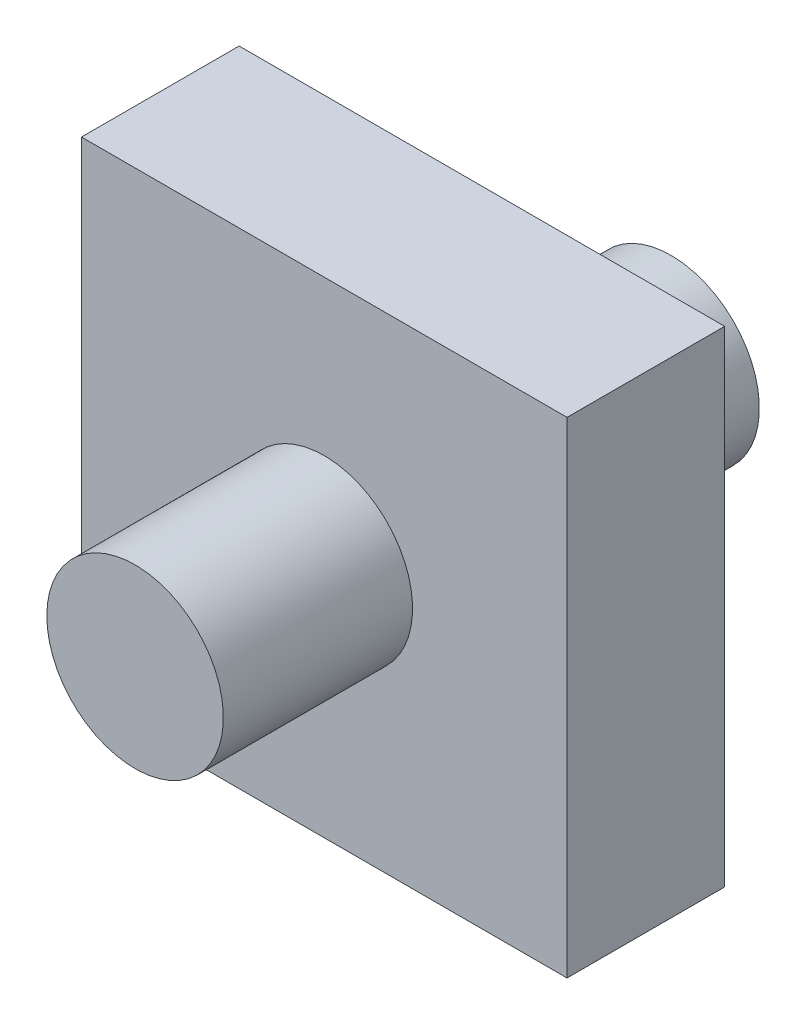
SolidWorks part; units mm, degrees
ref_plane "Alzado" through (0, 0, 0) normal (0, 0, 1) x (1, 0, 0)
ref_plane "Planta" through (0, 0, 0) normal (0, 1, 0) x (1, 0, 0)
ref_plane "Vista lateral" through (0, 0, 0) normal (1, 0, 0) x (0, 0, -1)
sketch "Croquis1" plane through (0, 0, 0) normal (0, 0, 1) x (1, 0, 0)
  line L1 (-3.85, -3.85) -> (3.85, -3.85)
  line L2 (-3.85, -3.85) -> (-3.85, 3.85)
  line L3 (-3.85, 3.85) -> (3.85, 3.85)
  line L4 (3.85, -3.85) -> (3.85, 3.85)
  line L5 (-3.85, -3.85) -> (3.85, 3.85) construction
  line L6 (-3.85, 3.85) -> (3.85, -3.85) construction
  point P0 (0, 0)
  dimension "D1" = 7.7
  dimension "D2" = 7.7
extrude "Saliente-Extruir1" add sketch "Croquis1" along normal blind 2.5
sketch "Croquis2" plane through (0, 0, 0) normal (0, 0, -1) x (-1, 0, 0)
  circle A0 centre (0, 0) radius 1.4
  dimension "D1" = 2.8
extrude "Saliente-Extruir2" add sketch "Croquis2" along normal blind 3
ref_plane "Plano2" through (0, 0, 1.25) normal (0, 0, -1) x (-1, 0, 0)
sketch "Croquis6" plane through (0, 0, -3) normal (0, 0, -1) x (-1, 0, 0)
  circle A0 centre (0, 0) radius 0.6
  dimension "D1" = 1.2
extrude "Cortar-Extruir1" cut sketch "Croquis6" against normal through all
mirror "Simetría3" about plane through (0, 0, 1.25) normal (0, 0, -1) of "Saliente-Extruir2"
